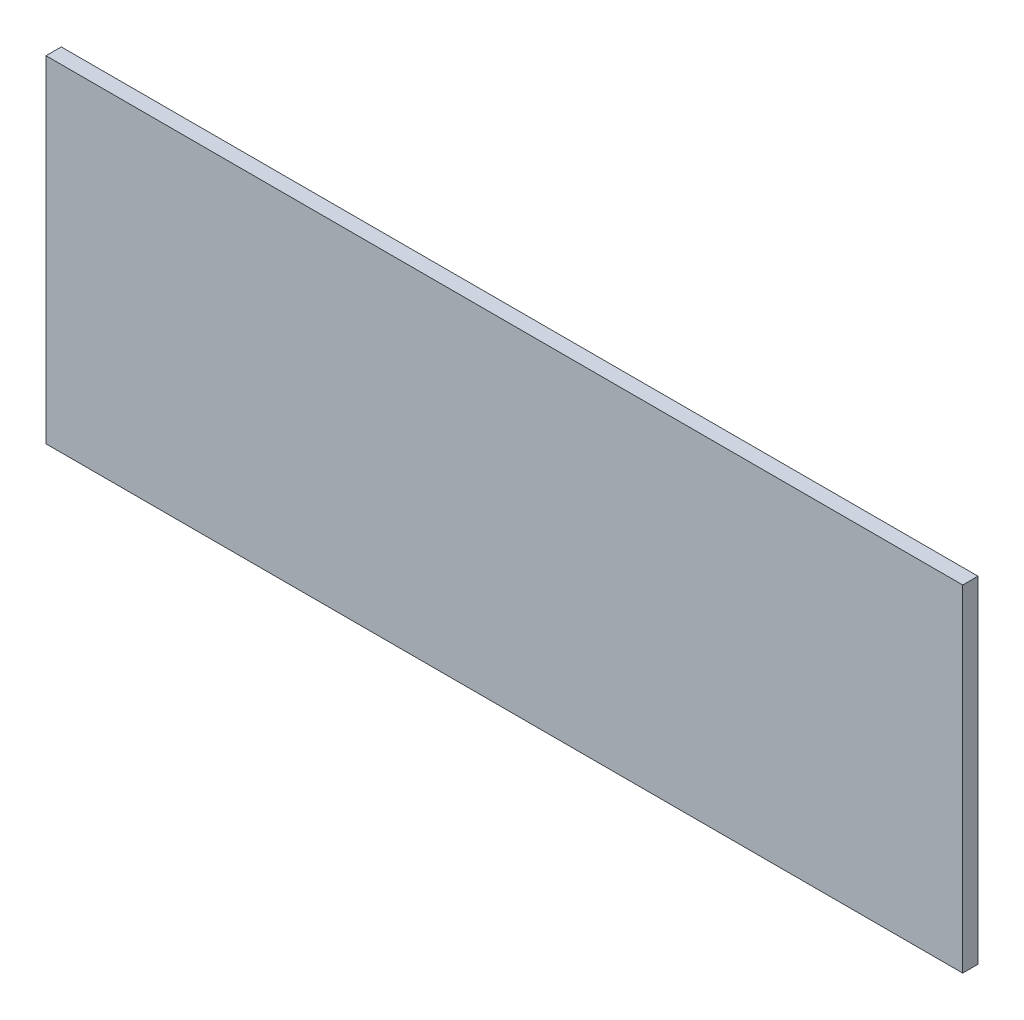
SolidWorks part; units mm, degrees
ref_plane "Front Plane" through (0, 0, 0) normal (0, 0, 1) x (1, 0, 0)
ref_plane "Top Plane" through (0, 0, 0) normal (0, 1, 0) x (1, 0, 0)
ref_plane "Right Plane" through (0, 0, 0) normal (1, 0, 0) x (0, 0, -1)
sketch "Sketch1" plane through (0, 0, 0) normal (0, 0, 1) x (1, 0, 0)
  line L1 (-90, -33) -> (90, -33)
  line L2 (-90, -33) -> (-90, 33)
  line L3 (-90, 33) -> (90, 33)
  line L4 (90, -33) -> (90, 33)
  line L5 (-90, -33) -> (90, 33) construction
  line L6 (-90, 33) -> (90, -33) construction
  point P0 (0, 0)
  dimension "D1" = 180
  dimension "D2" = 66
extrude "Boss-Extrude1" add sketch "Sketch1" along normal blind 3
